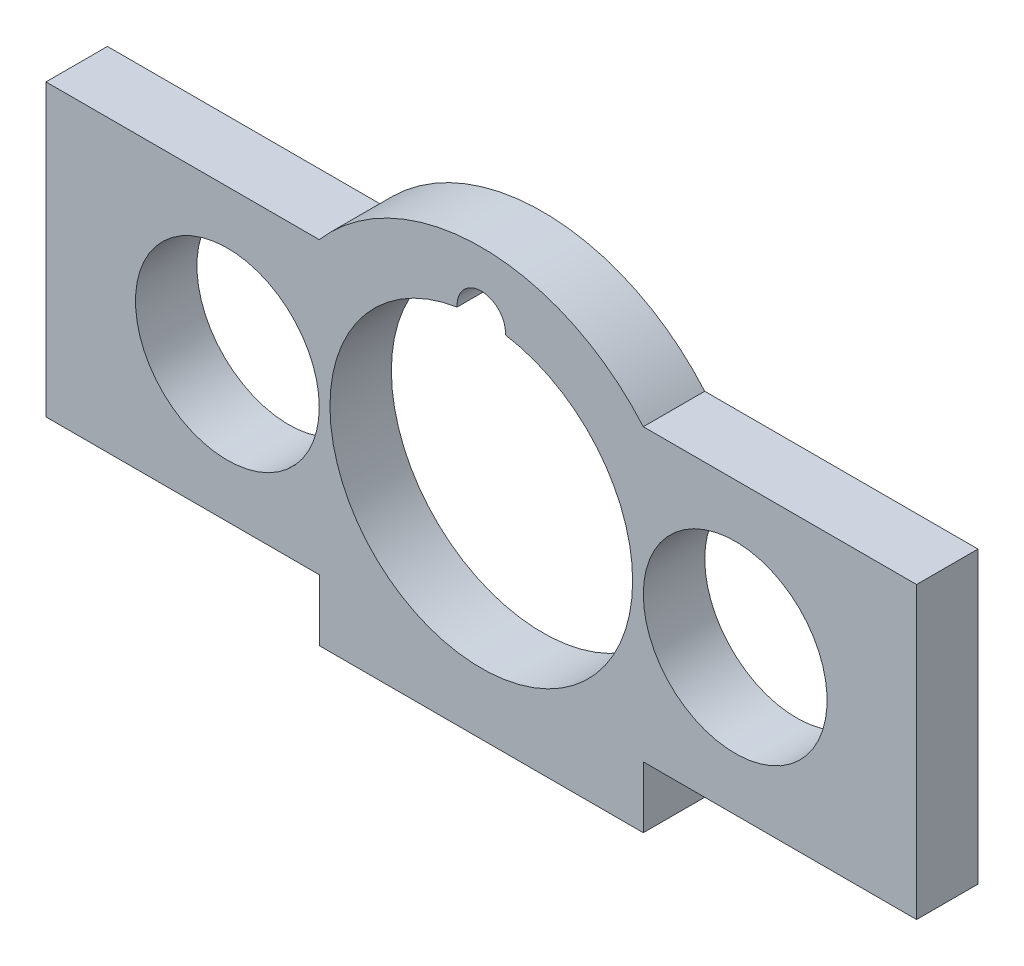
SolidWorks part; units mm, degrees
ref_plane "Front Plane" through (0, 0, 0) normal (0, 0, 1) x (1, 0, 0)
ref_plane "Top Plane" through (0, 0, 0) normal (0, 1, 0) x (1, 0, 0)
ref_plane "Right Plane" through (0, 0, 0) normal (1, 0, 0) x (0, 0, -1)
sketch "Sketch1" plane through (0, 0, 0) normal (0, 0, 1) x (1, 0, 0)
  line L0 (-18, -6.2586) -> (-18, 5.7414)
  line L1 (-18, 5.7414) -> (-6.7, 5.7414)
  line L2 (-18, -6.2586) -> (-6.7, -6.2586)
  line L3 (-6.7, -6.2586) -> (-6.7, -8.7986)
  line L4 (-6.7, -8.7986) -> (6.7, -8.7986)
  line L6 (0, 12.3064) -> (0, -16.7092) construction
  line L8 (6.7, -6.2586) -> (6.7, -8.7986)
  line L9 (18, -6.2586) -> (6.7, -6.2586)
  line L10 (18, 5.7414) -> (6.7, 5.7414)
  line L11 (18, -6.2586) -> (18, 5.7414)
  arc A0 (0.9974, 6.1786) -> (-0.9974, 6.1786) centre (0, 0) cw
  arc A1 (6.7, 5.7414) -> (-6.7, 5.7414) centre (0, 0) ccw
  circle A2 centre (-10.5, -0.2586) radius 3.8
  arc A3 (0.9974, 6.1786) -> (-0.9974, 6.1786) centre (0, 6.25) ccw
  circle A4 centre (10.5, -0.2586) radius 3.8
  dimension "D8" = 7.6
  dimension "D9" = 1
  dimension "D11" = 11.3
  dimension "D12" = 7.6
  dimension "D2" = 18
  dimension "D3" = 12
  dimension "D4" = 11.3
  dimension "D5" = 2.54
  dimension "D6" = 6
  dimension "D7" = 7.5
  dimension "D10" = 6.25
  dimension "D13" = 7.5
  dimension "D14" = 6
extrude "Base" add sketch "Sketch1" along normal blind 2.54
